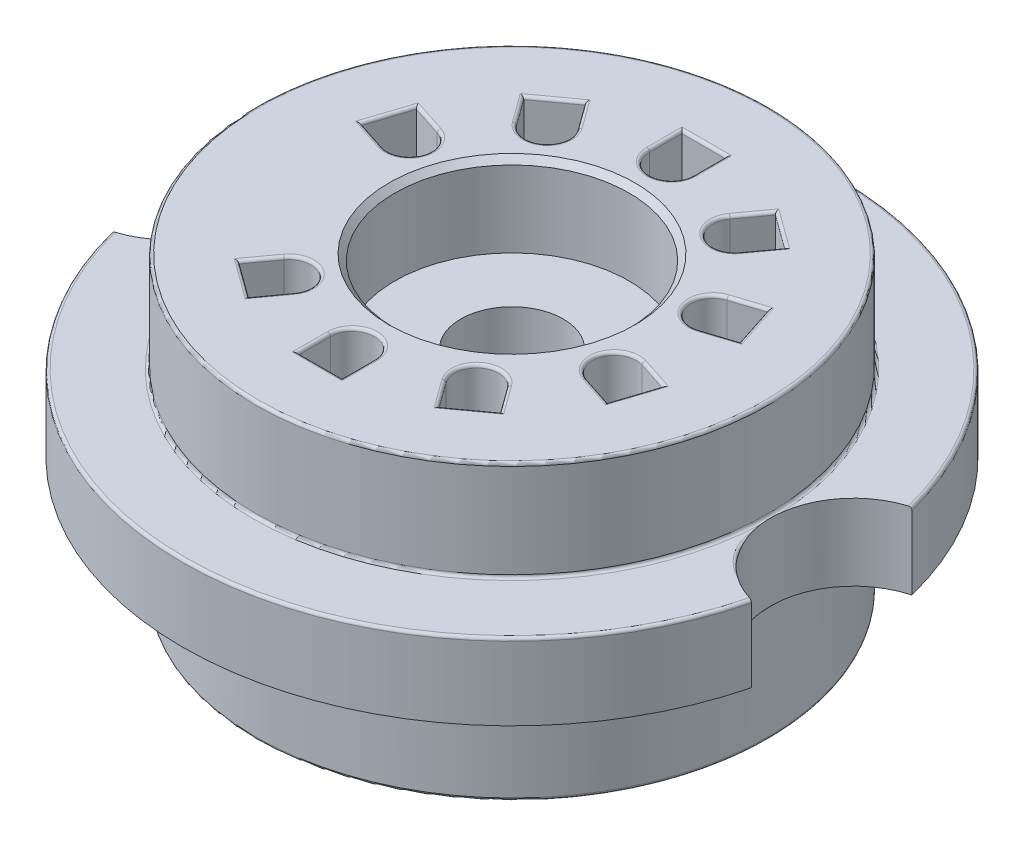
SolidWorks part; units mm, degrees
ref_plane "Plano frontal" through (0, 0, 0) normal (0, 0, 1) x (1, 0, 0)
ref_plane "Plano superior" through (0, 0, 0) normal (0, 1, 0) x (1, 0, 0)
ref_plane "Plano direito" through (0, 0, 0) normal (1, 0, 0) x (0, 0, -1)
sketch "Esboço1" plane through (0, 0, 0) normal (0, 1, 0) x (1, 0, 0)
  line L1 (-0.75, 5.4472) -> (-0.75, 6.5528)
  line L2 (0.75, 5.4472) -> (0.75, 6.5528)
  line L3 (-0.75, 6.5528) -> (0.75, 6.5528)
  line L4 (3.2449, 5.7422) -> (4.4584, 4.8605)
  line L6 (2.595, 4.8477) -> (3.2449, 5.7422)
  line L7 (3.8085, 3.966) -> (4.4584, 4.8605)
  line L8 (6.0003, 2.7382) -> (6.4638, 1.3116)
  line L10 (4.9488, 2.3966) -> (6.0003, 2.7382)
  line L11 (5.4124, 0.97) -> (6.4638, 1.3116)
  line L12 (6.4638, -1.3116) -> (6.0003, -2.7382)
  line L14 (5.4124, -0.97) -> (6.4638, -1.3116)
  line L15 (4.9488, -2.3966) -> (6.0003, -2.7382)
  line L16 (4.4584, -4.8605) -> (3.2449, -5.7422)
  line L18 (3.8085, -3.966) -> (4.4584, -4.8605)
  line L19 (2.595, -4.8477) -> (3.2449, -5.7422)
  line L20 (0.75, -6.5528) -> (-0.75, -6.5528)
  line L22 (0.75, -5.4472) -> (0.75, -6.5528)
  line L23 (-0.75, -5.4472) -> (-0.75, -6.5528)
  line L24 (-3.2449, -5.7422) -> (-4.4584, -4.8605)
  line L25 (8.9989, 0) -> (9, 0)
  line L26 (-2.595, -4.8477) -> (-3.2449, -5.7422)
  line L27 (-3.8085, -3.966) -> (-4.4584, -4.8605)
  line L32 (-6.4638, 1.3116) -> (-6.0003, 2.7382)
  line L33 (-8.99, -0.4251) -> (-8.9892, -0.4251)
  line L34 (-5.4124, 0.97) -> (-6.4638, 1.3116)
  line L35 (-4.9488, 2.3966) -> (-6.0003, 2.7382)
  line L36 (-4.4584, 4.8605) -> (-3.2449, 5.7422)
  line L38 (-3.8085, 3.966) -> (-4.4584, 4.8605)
  line L39 (-2.595, 4.8477) -> (-3.2449, 5.7422)
  line L43 (-6.2321, -2.0249) -> (-6.4638, -1.3116) [skipped]
  line L46 (10.7384, -2.3982) -> (10.9914, -2.3983)
  circle A0 centre (0, 0) radius 11.25
  arc A1 (-11.1733, 1.3116) -> (-10.9918, -2.3966) centre (-10.8563, -0.5314) cw
  arc A2 (-0.75, 5.4472) -> (0.75, 5.4472) centre (0, 5.4472) ccw
  arc A3 (11.1733, 1.3116) -> (10.9914, -2.3983) centre (10.865, -0.5327) ccw
  arc A4 (2.595, 4.8477) -> (3.8085, 3.966) centre (3.2018, 4.4069) ccw
  arc A5 (-8.9916, -0.3889) -> (-8.9866, -0.491) centre (0, 0) ccw
  arc A6 (4.9488, 2.3966) -> (5.4124, 0.97) centre (5.1806, 1.6833) ccw
  circle A7 centre (0, 0) radius 1.75
  arc A8 (5.4124, -0.97) -> (4.9488, -2.3966) centre (5.1806, -1.6833) ccw
  arc A10 (3.8085, -3.966) -> (2.595, -4.8477) centre (3.2018, -4.4069) ccw
  arc A12 (0.75, -5.4472) -> (-0.75, -5.4472) centre (0, -5.4472) ccw
  arc A14 (-2.595, -4.8477) -> (-3.8085, -3.966) centre (-3.2018, -4.4069) ccw
  arc A18 (-5.4124, 0.97) -> (-4.9488, 2.3966) centre (-5.1806, 1.6833) ccw
  arc A20 (-3.8085, 3.966) -> (-2.595, 4.8477) centre (-3.2018, 4.4069) ccw
  point P6 (0, 6)
  point P15 (-5.7063, -1.8541)
  point P18 (3.5267, 4.8541)
  point P27 (5.7063, 1.8541)
  point P32 (-11.25, 0)
  point P36 (5.7063, -1.8541)
  point P45 (3.5267, -4.8541)
  point P54 (0, -6)
  point P63 (-3.5267, -4.8541)
  point P72 (-5.7063, -1.8541)
  point P73 (-5.7063, 1.8541)
  point P81 (-5.7063, 1.8541)
  point P87 (-3.5267, 4.8541)
  point P90 (-3.5267, 4.8541)
  point P97 (0, 0)
  dimension "D1" = 22.5
  dimension "D2" = 3.5
  dimension "D5" = 18
  dimension "D3" = 1.5
  dimension "D4" = 10
extrude "Ressalto-extrusão1" add sketch "Esboço1" along normal blind 10
sketch "Esboço2" plane through (0, 10, 0) normal (0, 1, 0) x (1, 0, 0)
  circle A0 centre (0, 0) radius 8.75
  circle A1 centre (0, 0) radius 13.1985
  dimension "D1" = 17.5
extrude "Corte-extrusão1" cut sketch "Esboço2" against normal blind 3.4
sketch "Esboço3" plane through (0, 0, 0) normal (0, -1, 0) x (1, 0, 0)
  circle A0 centre (0, 0) radius 8.75
  circle A1 centre (0, 0) radius 12.5
  dimension "D1" = 17.5
  dimension "D2" = 25
extrude "Corte-extrusão2" cut sketch "Esboço3" against normal blind 4
fillet "Filete2" radius 0.1 5 edges at (0, 6.6, 8.75) (8.9974, 6.6, 0.4411) (0, 6.6, -11.25) (-0.0009, 6.6, 11.25) (-8.9884, 6.6, 0.44)
fillet "Filete3" radius 0.1 38 edges at (0, 10, 8.75) (-2.9199, 10, -5.2949) (-3.8516, 10, -5.3013) (-4.1335, 10, -4.4133) (-2.7609, 10, -3.8001) (-5.4746, 10, -2.5674) (-6.2321, 10, -2.0249) (-5.9381, 10, -1.1408) (-4.4673, 10, -1.4515) (-4.1335, 10, 4.4133) (-3.8516, 10, 5.3013) (-2.9199, 10, 5.2949) (-2.7609, 10, 3.8001) (-0.75, 10, 6) (0, 10, 6.5528) (0.75, 10, 6) (0, 10, 4.6972) (2.9199, 10, 5.2949) (3.8516, 10, 5.3013) (4.1335, 10, 4.4133) (2.7609, 10, 3.8001) (5.4746, 10, 2.5674) (6.2321, 10, 2.0249) (5.9381, 10, 1.1408) (4.4673, 10, 1.4515) (0, 10, 1.75) (5.9381, 10, -1.1408) (6.2321, 10, -2.0249) (5.4746, 10, -2.5674) (4.4673, 10, -1.4515) (4.1335, 10, -4.4133) (3.8516, 10, -5.3013) (2.9199, 10, -5.2949) (2.7609, 10, -3.8001) (0.75, 10, -6) (0, 10, -6.5528) (-0.75, 10, -6) (0, 10, -4.6972)
fillet "Filete4" radius 0.1 2 edges at (0, 0, -8.75) (0, 4, -8.75)
sketch "Esboço4" plane through (0, 0, 0) normal (0, -1, 0) x (1, 0, 0)
  circle A0 centre (0, 0) radius 10.1406
extrude "Ressalto-extrusão2" add sketch "Esboço4" along normal blind 0.001
sketch "Esboço5" plane through (0, 0, 0) normal (0, 1, 0) x (1, 0, 0)
  line L0 (4.1335, 4.4133) -> (2.9199, 5.2949)
  line L1 (3.8085, 3.966) -> (4.4584, 4.8605) construction
  line L2 (2.595, 4.8477) -> (3.2449, 5.7422) construction
  line L3 (-0.75, 6) -> (0.75, 6)
  line L4 (0.75, 5.4472) -> (0.75, 6.5528) construction
  line L5 (-5.9381, 1.1408) -> (-5.4124, 0.97)
  line L6 (0.75, 5.4472) -> (0.85, 5.4472) construction
  line L7 (-0.75, 5.4472) -> (-0.75, 6)
  line L8 (2.9199, 5.2949) -> (2.595, 4.8477)
  line L10 (4.1335, 4.4133) -> (3.8085, 3.966)
  line L11 (0.75, 5.4472) -> (0.75, 6)
  line L12 (5.4746, 2.5674) -> (4.9488, 2.3966)
  line L13 (5.4124, 0.97) -> (6.4638, 1.3116) construction
  line L14 (5.9381, 1.1408) -> (5.4746, 2.5674)
  line L15 (4.9488, 2.3966) -> (6.0003, 2.7382) construction
  line L16 (5.9381, 1.1408) -> (5.4124, 0.97)
  line L20 (5.4124, -0.97) -> (6.4638, -1.3116) construction
  line L21 (5.9381, -1.1408) -> (5.4746, -2.5674)
  line L22 (4.9488, -2.3966) -> (6.0003, -2.7382) construction
  line L24 (-2.595, 4.8477) -> (-3.2449, 5.7422) construction
  line L25 (-5.4746, 2.5674) -> (-4.9488, 2.3966)
  line L27 (2.595, -4.8477) -> (3.2449, -5.7422) construction
  line L28 (2.9199, -5.2949) -> (4.1335, -4.4133)
  line L30 (3.8085, -3.966) -> (4.4584, -4.8605) construction
  line L31 (3.8085, -3.966) -> (4.1335, -4.4133)
  line L32 (-0.75, -5.4472) -> (-0.75, -6.5528) construction
  line L33 (-0.75, -6) -> (0.75, -6)
  line L34 (0.75, -5.4472) -> (0.75, -6.5528) construction
  line L35 (2.595, -4.8477) -> (2.9199, -5.2949)
  line L36 (-3.8085, 3.966) -> (-3.8894, 3.9073) construction
  line L37 (5.4124, -0.97) -> (5.9381, -1.1408)
  line L38 (-2.595, -4.8477) -> (-3.2449, -5.7422) construction
  line L40 (-2.9199, -5.2949) -> (-4.1335, -4.4133)
  line L41 (-3.8085, -3.966) -> (-4.4584, -4.8605) construction
  line L44 (-0.75, -5.4472) -> (-0.75, -6)
  line L46 (-4.9488, 2.3966) -> (-6.0003, 2.7382) construction
  line L47 (-5.4746, 2.5674) -> (-5.9381, 1.1408)
  line L48 (-5.4124, 0.97) -> (-6.4638, 1.3116) construction
  line L52 (-3.8085, 3.966) -> (-4.1335, 4.4133)
  line L53 (-3.8085, 3.966) -> (-4.4584, 4.8605) construction
  line L54 (-4.1335, 4.4133) -> (-2.9199, 5.2949)
  line L55 (-2.595, 4.8477) -> (-3.2449, 5.7422) construction
  line L56 (-2.9199, 5.2949) -> (-2.595, 4.8477)
  line L57 (-3.8085, -3.966) -> (-4.1335, -4.4133)
  line L58 (0.75, -5.4472) -> (0.75, -6)
  line L59 (4.9488, -2.3966) -> (5.4746, -2.5674)
  line L60 (-2.595, -4.8477) -> (-2.9199, -5.2949)
  arc A0 (3.8085, -3.966) -> (2.595, -4.8477) centre (3.2018, -4.4069) ccw
  arc A1 (0.75, -5.4472) -> (-0.75, -5.4472) centre (0, -5.4472) ccw construction
  arc A2 (0.75, -5.4472) -> (-0.75, -5.4472) centre (0, -5.4472) ccw construction
  arc A3 (5.4124, -0.97) -> (4.9488, -2.3966) centre (5.1806, -1.6833) ccw
  arc A4 (-0.75, -5.4472) -> (0.75, -5.4472) centre (0, -5.4472) cw
  arc A5 (4.9488, 2.3966) -> (5.4124, 0.97) centre (5.1806, 1.6833) ccw
  arc A6 (2.595, 4.8477) -> (3.8085, 3.966) centre (3.2018, 4.4069) ccw
  arc A7 (-0.75, 5.4472) -> (0.75, 5.4472) centre (0, 5.4472) ccw construction
  arc A8 (-0.75, 5.4472) -> (0.75, 5.4472) centre (0, 5.4472) ccw
  arc A9 (-3.8085, 3.966) -> (-2.595, 4.8477) centre (-3.2018, 4.4069) ccw construction
  arc A10 (-2.595, 4.8477) -> (-2.6932, 3.8557) centre (-3.2018, 4.4069) cw
  arc A11 (-4.9488, 2.3966) -> (-4.4673, 1.4515) centre (-5.1806, 1.6833) cw
  arc A12 (-2.595, -4.8477) -> (-3.8085, -3.966) centre (-3.2018, -4.4069) ccw
  arc A13 (-5.4124, 0.97) -> (-4.9488, 2.3966) centre (-5.1806, 1.6833) ccw construction
  arc A14 (-4.4673, 1.4515) -> (-5.4124, 0.97) centre (-5.1806, 1.6833) cw
  arc A15 (-2.6932, 3.8557) -> (-3.8085, 3.966) centre (-3.2018, 4.4069) cw
  point P15 (0, 6)
extrude "Ressalto-extrusão11" add sketch "Esboço5" along normal blind 5.1
sketch "Esboço11" plane through (0, 0, 0) normal (1, 0, 0) x (0, 0, -1)
  line L3 (13.0167, 0) -> (-12.704, 0)
  line L4 (13.0167, 0) -> (13.7724, -2.9226)
  line L5 (13.7724, -2.9226) -> (-13.3555, -1.6717)
  line L6 (-13.3555, -1.6717) -> (-12.704, 0)
extrude "Corte-extrusão8" cut sketch "Esboço11" against normal blind 14.1 and the other way blind 14
sketch "Esboço12" plane through (0, 10, 0) normal (0, 1, 0) x (1, 0, 0)
  circle A0 centre (0, 0) radius 3.0216
extrude "Corte-extrusão9" cut sketch "Esboço12" against normal blind 2.5
sketch "Esboço13" plane through (0, 10, 0) normal (0, 1, 0) x (1, 0, 0)
  circle A0 centre (0, 0) radius 4
  dimension "D1" = 8
extrude "Corte-extrusão10" cut sketch "Esboço13" against normal blind 2.8
chamfer "Chanfro1" distance 0.2 angle 45 1 edges at (0, 10, 4)
sketch "Esboço14" plane through (0, 6.6, 0) normal (0, 1, 0) x (1, 0, 0)
  line L4 (8.8409, -9.6624) -> (8.8409, -9.1465)
  line L11 (-11.1803, -2.8) -> (-11.0442, -2.8)
  line L18 (-11.1803, -2.8) -> (-11.1803, 2.8)
  line L20 (11.1803, -2.8) -> (11.1803, 2.8)
  arc A0 (-11.1803, 2.8) -> (-11.0442, -2.8) centre (-11.6834, -0.0139) cw
  arc A2 (11.1803, 2.8) -> (11.1803, -2.8) centre (11.6632, 0) ccw
  point P0 (0, 0)
  circle M1 centre (0, 0) radius 8.85
  arc M3 (10.8655, -2.5025) -> (11.0582, 1.4277) centre (10.865, -0.5327) cw
  arc M4 (11.0582, 1.4277) -> (-11.0581, 1.4283) centre (0, 0) ccw
extrude "Corte-extrusão11" cut sketch "Esboço14" along normal blind 6 and the other way blind 14 contours A2 M4 M1 M3 | L18 A0 L11
